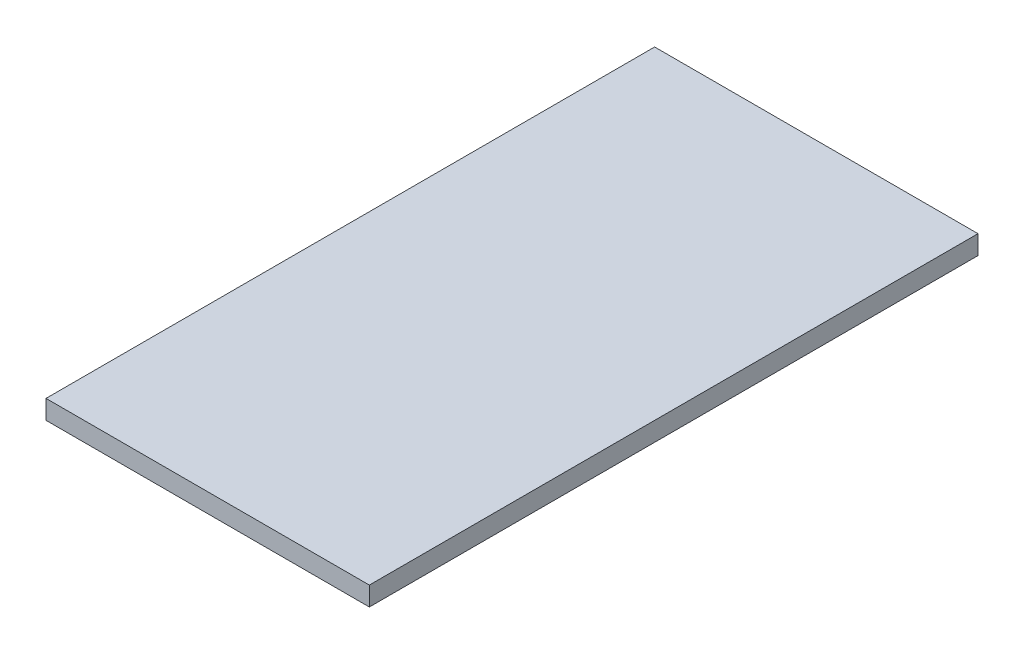
SolidWorks part; units mm, degrees
ref_plane "정면" through (0, 0, 0) normal (0, 0, 1) x (1, 0, 0)
ref_plane "윗면" through (0, 0, 0) normal (0, 1, 0) x (1, 0, 0)
ref_plane "우측면" through (0, 0, 0) normal (1, 0, 0) x (0, 0, -1)
sketch "스케치1" plane through (0, 0, 0) normal (0, 1, 0) x (1, 0, 0)
  line L1 (8.5, -16.5) -> (-8.5, -16.5)
  line L2 (8.5, -16.5) -> (8.5, 16.5)
  line L3 (8.5, 16.5) -> (-8.5, 16.5)
  line L4 (-8.5, -16.5) -> (-8.5, 16.5)
  line L5 (8.5, -16.5) -> (-8.5, 16.5) construction
  line L6 (8.5, 16.5) -> (-8.5, -16.5) construction
  point P0 (0, 0)
  dimension "D1" = 17
  dimension "D2" = 33
extrude "보스-돌출1" add sketch "스케치1" along normal blind 10
sketch "스케치2" plane through (0, 0, 0) normal (0, 1, 0) x (1, 0, 0)
  line L0 (-8.5, 16.5) -> (-8.5, -16.5) construction
  line L1 (-7.5, 16.5) -> (7.5, 16.5)
  line L2 (-7.5, 16.5) -> (-7.5, -15.5)
  line L3 (-7.5, -15.5) -> (7.5, -15.5)
  line L4 (7.5, 16.5) -> (7.5, -15.5)
  line L5 (-8.5, -16.5) -> (8.5, -16.5) construction
  dimension "D1" = 15
  dimension "D2" = 1
  dimension "D3" = 32
  dimension "D4" = 1
extrude "컷-돌출1" cut sketch "스케치2" along normal blind 8 from offset 1
sketch "스케치3" plane through (0, 0, 0) normal (0, 0, 1) x (1, 0, 0)
  line L0 (-8.5, 0) -> (8.5, 0) construction
  circle A0 centre (0, 6) radius 3
  dimension "D1" = 3
  dimension "D2" = 6
extrude "컷-돌출2" cut sketch "스케치3" along normal through all
sketch "스케치5" plane through (0, 0, 0) normal (0, 1, 0) x (1, 0, 0)
  line L0 (8.5, -16.5) -> (8.5, 16.5) construction
  line L1 (-8.5, 16.5) -> (8.5, 16.5)
  line L2 (-8.5, 16.5) -> (-8.5, -15.5)
  line L3 (-8.5, -15.5) -> (8.5, -15.5)
  line L4 (8.5, 16.5) -> (8.5, -15.5)
  line L5 (-8.5, -16.5) -> (8.5, -16.5) construction
  dimension "D1" = 1
extrude "컷-돌출3" cut sketch "스케치5" along normal blind 8 from offset 9
sketch "스케치6" plane through (0, 0, 0) normal (0, 1, 0) x (1, 0, 0)
  line L1 (-8.5, 16.5) -> (8.5, 16.5)
  line L2 (-8.5, 16.5) -> (-8.5, -15.5)
  line L3 (-8.5, -15.5) -> (8.5, -15.5)
  line L4 (8.5, 16.5) -> (8.5, -15.5)
extrude "보스-돌출2" add sketch "스케치6" along normal blind 1 from offset 9 separate body
sketch "스케치8" plane through (0, 0, 0) normal (0, -1, 0) x (1, 0, 0)
  line L4 (-8.5, 16.5) -> (-8.5, -16.5)
  line L5 (-8.5, -16.5) -> (8.5, -16.5)
  line L6 (8.5, -16.5) -> (8.5, 16.5)
  line L7 (8.5, 16.5) -> (-8.5, 16.5)
  line L8 (-8.5, 16.5) -> (-8.5, -16.5)
  line L9 (-8.5, -16.5) -> (8.5, -16.5)
  line L10 (8.5, -16.5) -> (8.5, 16.5)
  line L11 (8.5, 16.5) -> (-8.5, 16.5)
  dimension "D1" = 0
extrude "컷-돌출5" cut sketch "스케치8" against normal blind 9
sketch "스케치9" plane through (0, 0, 16.5) normal (0, 0, 1) x (1, 0, 0)
  line L4 (-8.5, 9) -> (8.5, 9)
  line L5 (8.5, 9) -> (8.5, 10)
  line L6 (8.5, 10) -> (-8.5, 10)
  line L7 (-8.5, 10) -> (-8.5, 9)
  line L8 (-8.5, 9) -> (8.5, 9)
  line L9 (8.5, 9) -> (8.5, 10)
  line L10 (8.5, 10) -> (-8.5, 10)
  line L11 (-8.5, 10) -> (-8.5, 9)
  dimension "D1" = 0
extrude "컷-돌출6" cut sketch "스케치9" against normal blind 1
